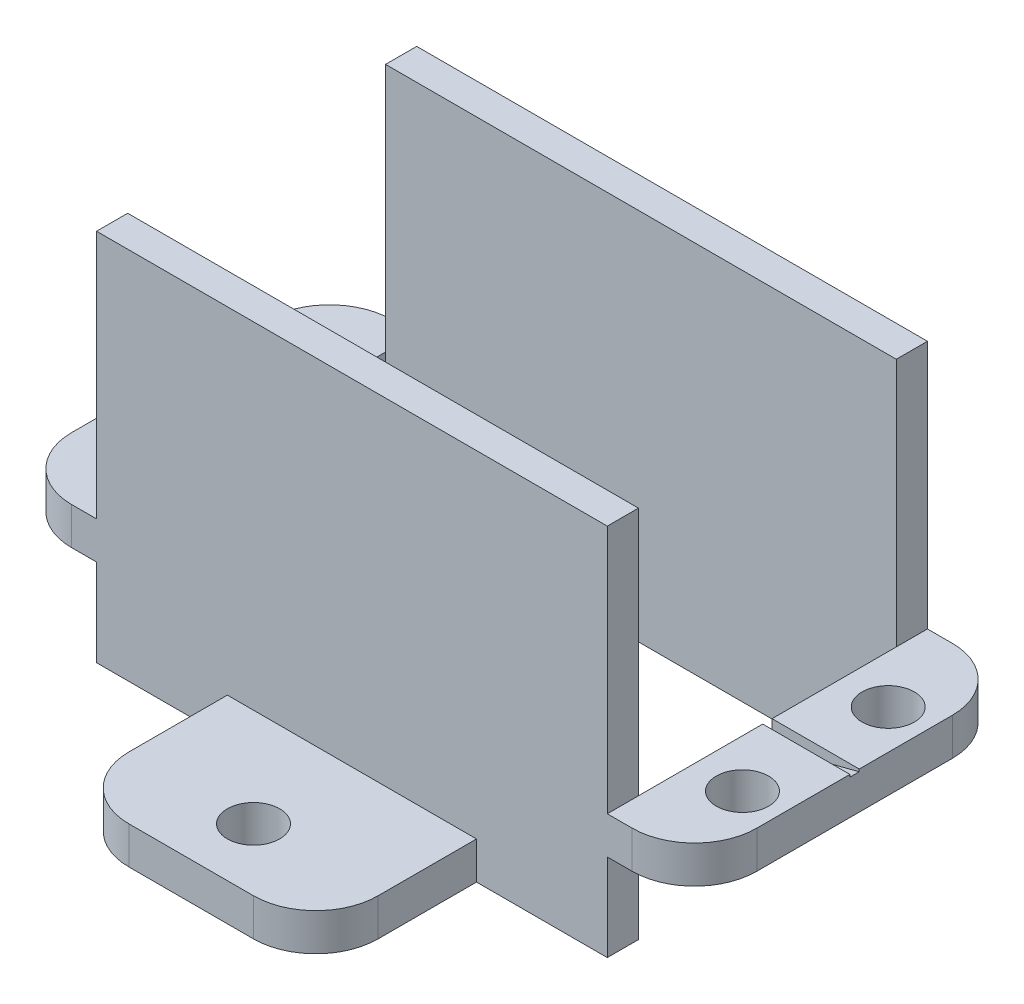
SolidWorks part; units mm, degrees
ref_plane "Front Plane" through (0, 0, 0) normal (0, 0, 1) x (1, 0, 0)
ref_plane "Top Plane" through (0, 0, 0) normal (0, 1, 0) x (1, 0, 0)
ref_plane "Right Plane" through (0, 0, 0) normal (1, 0, 0) x (0, 0, -1)
sketch "Sketch1" plane through (0, 0, 0) normal (0, 1, 0) x (1, 0, 0)
  line L1 (27.5, -12.85) -> (-27.5, -12.85)
  line L2 (27.5, -12.85) -> (27.5, 12.85)
  line L3 (27.5, 12.85) -> (-27.5, 12.85)
  line L4 (-27.5, -12.85) -> (-27.5, 12.85)
  line L5 (27.5, -12.85) -> (-27.5, 12.85) construction
  line L6 (27.5, 12.85) -> (-27.5, -12.85) construction
  point P0 (0, 0)
  dimension "D1" = 25.7
  dimension "D2" = 55
extrude "Boss-Extrude1" add sketch "Sketch1" along normal blind 3
sketch "Sketch2" plane through (0, 3, 0) normal (0, 1, 0) x (1, 0, 0)
  line L1 (20.5, -10.35) -> (-20.5, -10.35)
  line L2 (20.5, -10.35) -> (20.5, 10.35)
  line L3 (20.5, 10.35) -> (-20.5, 10.35)
  line L4 (-20.5, -10.35) -> (-20.5, 10.35)
  line L5 (20.5, -10.35) -> (-20.5, 10.35) construction
  line L6 (20.5, 10.35) -> (-20.5, -10.35) construction
  point P0 (0, 0)
  dimension "D1" = 20.7
  dimension "D2" = 41
extrude "Cut-Extrude1" cut sketch "Sketch2" against normal through all
sketch "Sketch3" plane through (0, 3, 0) normal (0, 1, 0) x (1, 0, 0)
  line L0 (27.5, 12.85) -> (-27.5, 12.85) construction
  line L1 (20.5, -10.35) -> (20.5, 10.35) construction
  circle A0 centre (24.35, 5.85) radius 2.1
  circle A1 centre (24.35, -5.85) radius 2.1
  dimension "D1" = 11.7
  dimension "D2" = 7
  dimension "D3" = 3.85
  dimension "D4" = 4.2
extrude "Cut-Extrude2" cut sketch "Sketch3" against normal through all
mirror "Mirror1" about plane through (0, 0, 0) normal (1, 0, 0) of "Cut-Extrude2"
sketch "Sketch4" plane through (0, 3, 0) normal (0, 1, 0) x (1, 0, 0)
  line L0 (-20.5, 10.35) -> (-20.5, 12.85)
  line L1 (27.5, 12.85) -> (-27.5, 12.85) construction
  line L2 (20.5, 10.35) -> (20.5, 12.85)
  line L3 (20.5, 12.85) -> (-20.5, 12.85)
  line L4 (20.5, 10.35) -> (-20.5, 10.35) construction
  line L5 (20.5, 10.35) -> (-20.5, 10.35)
  line L6 (-20.5, -10.35) -> (-20.5, -12.85)
  line L7 (-27.5, -12.85) -> (27.5, -12.85) construction
  line L8 (20.5, -10.35) -> (20.5, -12.85)
  line L9 (-20.5, -10.35) -> (20.5, -10.35) construction
  line L10 (-20.5, -10.35) -> (20.5, -10.35)
  line L11 (-20.5, -12.85) -> (20.5, -12.85)
extrude "Boss-Extrude2" add sketch "Sketch4" along normal blind 20
sketch "Sketch5" plane through (0, 0, 0) normal (0, 0, 1) x (1, 0, 0)
  line L0 (20.5, 1) -> (20.5, 3)
  line L1 (20.5, 23) -> (20.5, 3) construction
  line L2 (20.5, 3) -> (28.246, 3)
  line L3 (28.246, 3) -> (20.5, 1)
  point P4 (0, 0)
  dimension "D1" = 2
  dimension "D2" = 8
extrude "Cut-Extrude3" cut sketch "Sketch5" against normal mid plane 0.75
mirror "Mirror2" about plane through (0, 0, 0) normal (1, 0, 0) of "Cut-Extrude3"
fillet "Fillet1" radius 5 4 edges at (-27.5, 1.5, 12.85) (-27.5, 1.5, -12.85) (27.5, 1.5, -12.85) (27.5, 1.5, 12.85)
sketch "Sketch6" plane through (0, 0, 0) normal (0, -1, 0) x (1, 0, 0)
  line L1 (-20.5, 10.35) -> (20.5, 10.35)
  line L2 (-20.5, 10.35) -> (-20.5, 12.85)
  line L3 (-20.5, 12.85) -> (20.5, 12.85)
  line L4 (20.5, 10.35) -> (20.5, 12.85)
  line L5 (-20.5, -10.35) -> (20.5, -10.35)
  line L6 (-20.5, -10.35) -> (-20.5, -12.85)
  line L7 (-20.5, -12.85) -> (20.5, -12.85)
  line L8 (20.5, -10.35) -> (20.5, -12.85)
extrude "Boss-Extrude3" add sketch "Sketch6" along normal blind 7
sketch "Sketch7" plane through (0, 0, 12.85) normal (0, 0, 1) x (1, 0, 0)
  line L0 (20.5, -7) -> (-20.5, -7) construction
  line L1 (-10, -7) -> (10, -7)
  line L2 (-10, -7) -> (-10, -4)
  line L3 (-10, -4) -> (10, -4)
  line L4 (10, -7) -> (10, -4)
  point P6 (0, -4)
  dimension "D1" = 20
  dimension "D2" = 3
extrude "Boss-Extrude4" add sketch "Sketch7" along normal blind 12.9
sketch "Sketch8" plane through (0, -4, 0) normal (0, 1, 0) x (1, 0, 0)
  line L0 (-10, -25.75) -> (-10, -12.85) construction
  line L2 (10, -12.85) -> (-10, -12.85) construction
  circle A0 centre (0, -20.75) radius 2.1
  dimension "D1" = 4.2
  dimension "D2" = 10
  dimension "D3" = 7.9
extrude "Cut-Extrude4" cut sketch "Sketch8" against normal through all
fillet "Fillet2" radius 5 2 edges at (-10, -5.5, 25.75) (10, -5.5, 25.75)
mirror "Mirror5" about plane through (0, 0, 0) normal (0, 0, 1) of "Boss-Extrude4", "Fillet2", "Cut-Extrude4"
sketch "Sketch9" plane through (0, -7, 0) normal (0, -1, 0) x (1, 0, 0)
  point P0 (0, 20.75)
  point P1 (0, -20.75)
